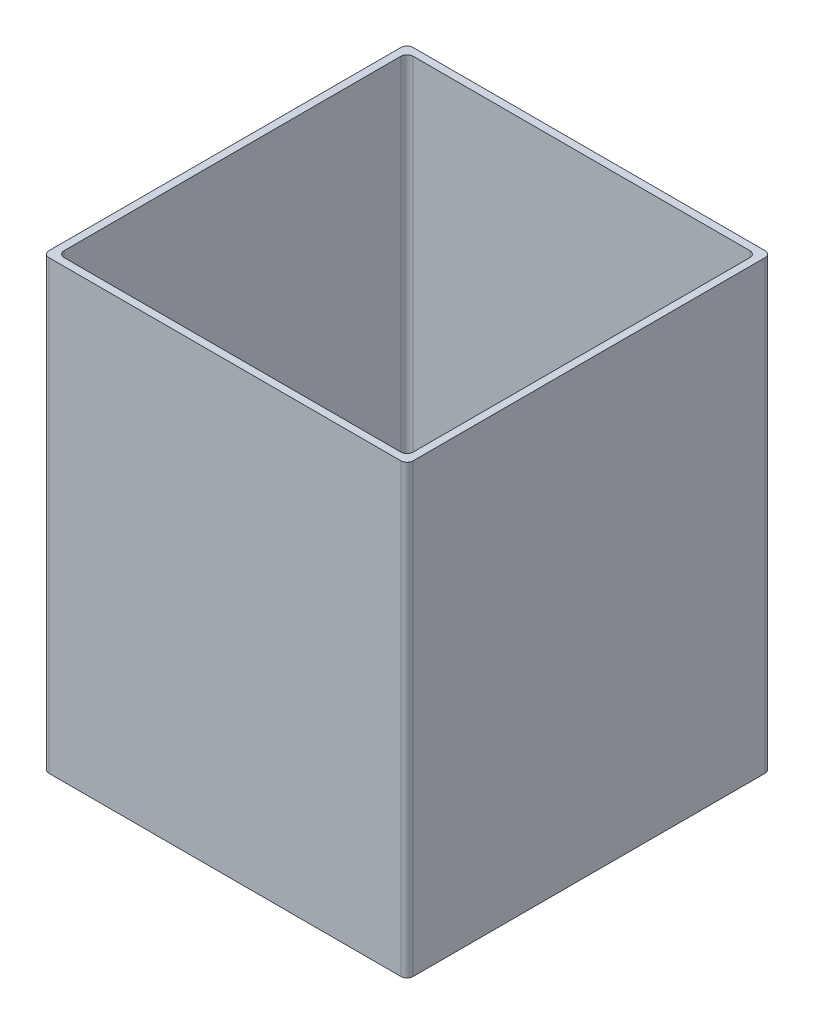
SolidWorks part; units mm, degrees
material "ABS"
ref_plane "Plano frontal" through (0, 0, 0) normal (0, 0, 1) x (1, 0, 0)
ref_plane "Plano superior" through (0, 0, 0) normal (0, 1, 0) x (1, 0, 0)
ref_plane "Plano direito" through (0, 0, 0) normal (1, 0, 0) x (0, 0, -1)
sketch "Esboço2" plane through (0, 0, 0) normal (0, 1, 0) x (1, 0, 0)
  line L1 (-60, 60) -> (60, 60)
  line L2 (-60, 60) -> (-60, -60)
  line L3 (-60, -60) -> (60, -60)
  line L4 (60, 60) -> (60, -60)
  line L5 (-60, 60) -> (60, -60) construction
  line L6 (-60, -60) -> (60, 60) construction
  point P0 (0, 0)
  dimension "D1" = 120
  dimension "D2" = 120
  dimension "D3" = 120
extrude "Ressalto-extrusão1" add sketch "Esboço2" along normal blind 147.2
sketch "Esboço3" plane through (0, 147.2, 0) normal (0, 1, 0) x (1, 0, 0)
  line L1 (-57.5, 57.5) -> (57.5, 57.5)
  line L2 (-57.5, 57.5) -> (-57.5, -57.5)
  line L3 (-57.5, -57.5) -> (57.5, -57.5)
  line L4 (57.5, 57.5) -> (57.5, -57.5)
  line L5 (-57.5, 57.5) -> (57.5, -57.5) construction
  line L6 (-57.5, -57.5) -> (57.5, 57.5) construction
  point P0 (0, 0)
  dimension "D1" = 115
  dimension "D2" = 115
extrude "Corte-extrusão1" cut sketch "Esboço3" against normal through all both and the other way through all
fillet "Filete1" radius 2 4 edges at (60, 73.6, 60) (60, 73.6, -60) (-60, 73.6, 60) (-60, 73.6, -60)
fillet "Filete2" radius 2 4 edges at (57.5, 73.6, -57.5) (57.5, 73.6, 57.5) (-57.5, 73.6, 57.5) (-57.5, 73.6, -57.5)
